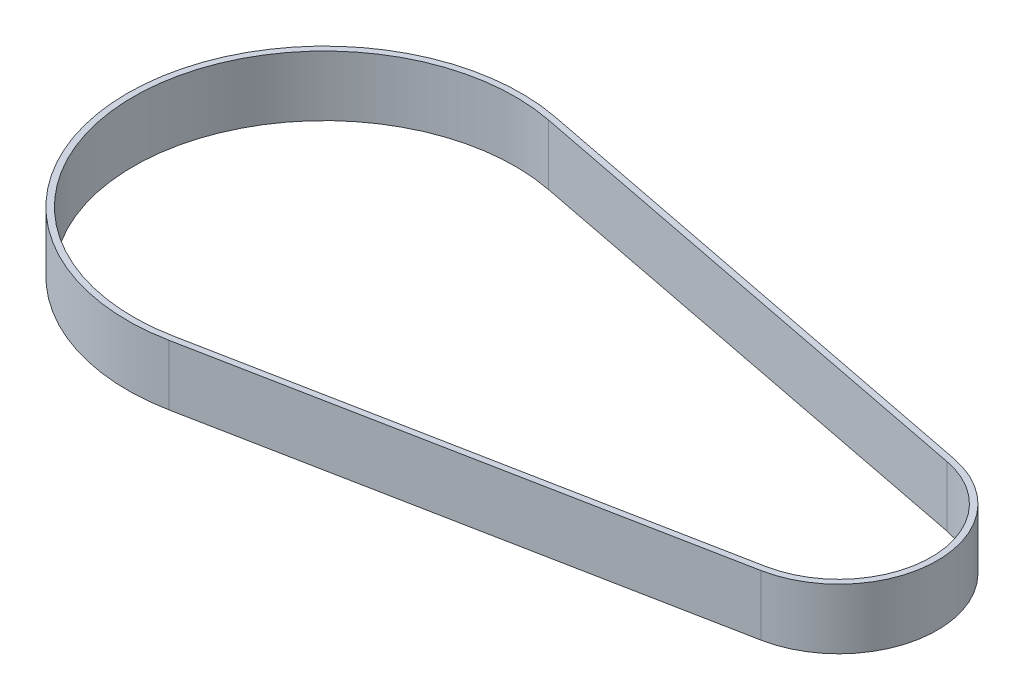
SolidWorks part; units mm, degrees
ref_plane "Front" through (0, 0, 0) normal (0, 0, 1) x (1, 0, 0)
ref_plane "Top" through (0, 0, 0) normal (0, 1, 0) x (1, 0, 0)
ref_plane "Right" through (0, 0, 0) normal (1, 0, 0) x (0, 0, -1)
sketch "草图1" plane through (0, 0, 0) normal (0, 1, 0) x (1, 0, 0)
  line L0 (0, 0) -> (128, 0) construction
  line L1 (9.0918, 46.6218) -> (132.4023, 22.5748)
  line L2 (9.0918, -46.6218) -> (132.4023, -22.5748)
  line L3 (9.3789, -48.094) -> (132.6895, -24.047)
  line L4 (9.3789, 48.094) -> (132.6895, 24.047)
  circle A0 centre (0, 0) radius 47.5 construction
  circle A1 centre (128, 0) radius 23 construction
  arc A2 (9.0918, 46.6218) -> (9.0918, -46.6218) centre (0, 0) ccw
  arc A3 (132.4023, 22.5748) -> (132.4023, -22.5748) centre (128, 0) cw
  arc A4 (9.3789, 48.094) -> (9.3789, -48.094) centre (0, 0) ccw
  arc A5 (132.6895, 24.047) -> (132.6895, -24.047) centre (128, 0) cw
  dimension "D1" = 95
  dimension "D2" = 46
  dimension "D3" = 128
  dimension "D4" = 1.5
extrude "凸台-拉伸1" add sketch "草图1" along normal blind 15
